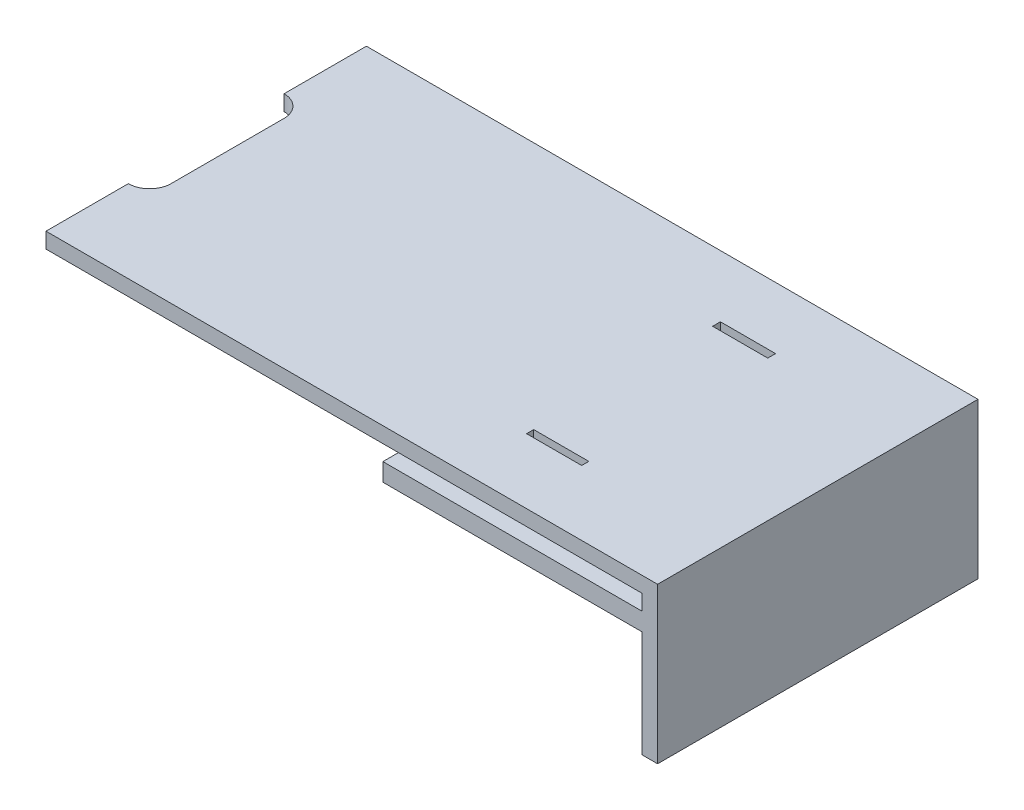
SolidWorks part; units mm, degrees
ref_plane "Front Plane" through (0, 0, 0) normal (0, 0, 1) x (1, 0, 0)
ref_plane "Top Plane" through (0, 0, 0) normal (0, 1, 0) x (1, 0, 0)
ref_plane "Right Plane" through (0, 0, 0) normal (1, 0, 0) x (0, 0, -1)
sketch "Sketch1" plane through (0, 0, 0) normal (0, 1, 0) x (1, 0, 0)
  line L1 (57.5, 30.91) -> (-57.5, 30.91)
  line L2 (57.5, 30.91) -> (57.5, -30.91)
  line L3 (57.5, -30.91) -> (-57.5, -30.91)
  line L4 (-57.5, 30.91) -> (-57.5, -30.91)
  line L5 (57.5, 30.91) -> (-57.5, -30.91) construction
  line L6 (57.5, -30.91) -> (-57.5, 30.91) construction
  point P0 (0, 0)
  dimension "D1" = 61.82
  dimension "D2" = 115
extrude "Boss-Extrude1" add sketch "Sketch1" along normal blind 3
sketch "Sketch2" plane through (0, 3, 0) normal (0, 1, 0) x (1, 0, 0)
  line L0 (-57.5, -30.91) -> (-57.5, -10.91)
  line L1 (-57.5, 30.91) -> (-57.5, -30.91) construction
  line L2 (-57.5, 30.91) -> (-57.5, 10.91)
  line L3 (-57.5, 10.91) -> (-57.5, -10.91) construction
  line L4 (-53.3802, 10.91) -> (-53.3802, -10.91)
  line L5 (-61.6198, 10.91) -> (-61.6198, -10.91)
  arc A0 (-53.3802, 10.91) -> (-61.6198, 10.91) centre (-57.5, 10.91) ccw
  arc A1 (-61.6198, -10.91) -> (-53.3802, -10.91) centre (-57.5, -10.91) ccw
  point P8 (-57.5, 0)
  line M3 (-57.5, 30.91) -> (-57.5, -30.91)
  dimension "D1" = 20
  dimension "D2" = 20
extrude "Cut-Extrude1" cut sketch "Sketch2" against normal blind 3 contours A1 L4 A0 L2 M3
sketch "Sketch3" plane through (57.5, 0, 0) normal (1, 0, 0) x (0, 0, -1)
  line L0 (-30.91, 3) -> (-30.91, -27)
  line L1 (30.91, 3) -> (30.91, -27)
  line L2 (-30.91, -27) -> (30.91, -27)
  line L3 (-30.91, 3) -> (30.91, 3)
  dimension "D1" = 30
  dimension "D2" = 30
extrude "Boss-Extrude2" add sketch "Sketch3" along normal blind 3
sketch "Sketch4" plane through (57.5, 0, 0) normal (-1, 0, 0) x (0, 0, 1)
  line L0 (30.91, 0) -> (30.91, -3)
  line L1 (30.91, 0) -> (30.91, -27) construction
  line L3 (30.91, -3) -> (20.91, -3)
  line L4 (30.91, -3) -> (30.91, -6.45)
  line L5 (30.91, -6.45) -> (20.91, -6.45)
  line L6 (20.91, -3) -> (20.91, -6.45)
  dimension "D1" = 3
  dimension "D2" = 10
  dimension "D3" = 3.45
extrude "Boss-Extrude3" add sketch "Sketch4" along normal blind 50 contours L3 L6 L5 L4
mirror "Mirror1" about plane through (0, 0, 0) normal (0, 0, 1) of "Boss-Extrude3"
sketch "Sketch5" plane through (0, 0, 0) normal (0, -1, 0) x (1, 0, 0)
  line L0 (0, 13.25) -> (-2, 13.25)
  line L1 (0, 13.25) -> (49, 13.25)
  line L2 (0, 13.25) -> (0, -13.25)
  line L3 (0, -13.25) -> (49, -13.25)
  line L4 (49, 13.25) -> (49, -13.25)
  line L5 (0, 13.25) -> (49, -13.25) construction
  line L6 (0, -13.25) -> (49, 13.25) construction
  line L7 (0, 13.25) -> (0, 7.25)
  line L8 (-2, 13.25) -> (-2, 7.25)
  line L9 (0, 7.25) -> (-2, 7.25)
  line L10 (0, -13.25) -> (-2, -13.25)
  line L11 (0, -13.25) -> (0, -7.25)
  line L12 (-2, -13.25) -> (-2, -7.25)
  line L13 (0, -7.25) -> (-2, -7.25)
  line L14 (0, 13.25) -> (6, 13.25)
  line L15 (0, 13.25) -> (0, 15.25)
  line L16 (6, 13.25) -> (6, 15.25)
  line L17 (0, 15.25) -> (6, 15.25)
  line L18 (49, 13.25) -> (49, 15.25)
  line L19 (49, 13.25) -> (43, 13.25)
  line L20 (49, 15.25) -> (43, 15.25)
  line L21 (43, 13.25) -> (43, 15.25)
  line L22 (49, 13.25) -> (49, 7.25)
  line L23 (49, 13.25) -> (51, 13.25)
  line L24 (49, 7.25) -> (51, 7.25)
  line L25 (51, 13.25) -> (51, 7.25)
  line L26 (49, -13.25) -> (51, -13.25)
  line L27 (49, -13.25) -> (49, -7.25)
  line L28 (51, -13.25) -> (51, -7.25)
  line L29 (49, -7.25) -> (51, -7.25)
  line L30 (49, -13.25) -> (49, -15.25)
  line L31 (49, -13.25) -> (43, -13.25)
  line L32 (49, -15.25) -> (43, -15.25)
  line L33 (43, -13.25) -> (43, -15.25)
  line L34 (0, -13.25) -> (0, -15.25)
  line L35 (0, -13.25) -> (6, -13.25)
  line L36 (0, -15.25) -> (6, -15.25)
  line L37 (6, -13.25) -> (6, -15.25)
  line L38 (-2, 13.25) -> (0, 13.25)
  point P0 (24.5, 0)
  dimension "D1" = 26.5
  dimension "D2" = 49
  dimension "D3" = 6
  dimension "D4" = 6
  dimension "D5" = 6
  dimension "D6" = 6
  dimension "D7" = 2
  dimension "D8" = 2
  dimension "D9" = 6
  dimension "D10" = 2
  dimension "D11" = 6
  dimension "D12" = 2
  dimension "D13" = 2
  dimension "D14" = 2
  dimension "D15" = 2
  dimension "D16" = 2
  dimension "D17" = 6
  dimension "D18" = 6
extrude "Boss-Extrude12" add sketch "Sketch5" along normal blind 5 contours L3 L33 L32 L30 | L37 L3 L34 L36 | L9 L2 L0 L8 | L25 L23 L4 L24
sketch "Sketch8" plane through (0, 0, 0) normal (0, -1, 0) x (1, 0, 0)
  line L0 (22.7009, 18.3866) -> (33.3325, 18.3866)
  line L1 (22.7009, 18.3866) -> (22.7009, 17.0107)
  line L2 (33.3325, 18.3866) -> (33.3325, 17.0107)
  line L3 (22.7009, 17.0107) -> (33.3325, 17.0107)
  line L4 (22.7009, -17.511) -> (33.3325, -17.511)
  line L5 (22.7009, -17.511) -> (22.7009, -19.012)
  line L6 (33.3325, -17.511) -> (33.3325, -19.012)
  line L7 (22.7009, -19.012) -> (33.3325, -19.012)
extrude "Cut-Extrude2" cut sketch "Sketch8" against normal blind 5
